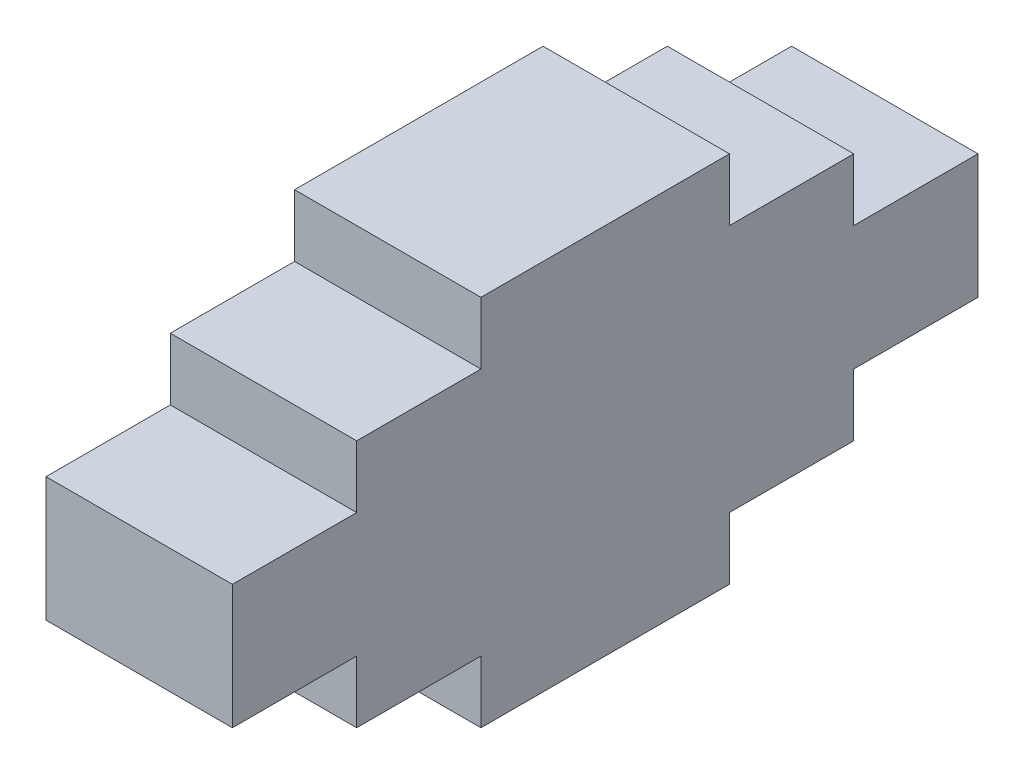
SolidWorks part; units mm, degrees
ref_plane "Front Plane" through (0, 0, 0) normal (0, 0, 1) x (1, 0, 0)
ref_plane "Top Plane" through (0, 0, 0) normal (0, 1, 0) x (1, 0, 0)
ref_plane "Right Plane" through (0, 0, 0) normal (1, 0, 0) x (0, 0, -1)
sketch "Sketch1" plane through (0, 0, 0) normal (1, 0, 0) x (0, 0, -1)
  line L0 (-84.64, 0) -> (83.36, 0) construction
  line L1 (0, 53.84) -> (0, -53.36) construction
  line L2 (-60, -10) -> (-60, 10)
  line L3 (-60, 10) -> (-40, 10)
  line L4 (-40, 10) -> (-40, 20)
  line L5 (-40, 20) -> (-20, 20)
  line L6 (-20, 20) -> (-20, 30)
  line L7 (-20, 30) -> (20, 30)
  line L8 (84.64, 0) -> (-83.36, 0) construction
  line L9 (20, 20) -> (20, 30)
  line L10 (40, 20) -> (20, 20)
  line L11 (40, 10) -> (40, 20)
  line L12 (60, 10) -> (40, 10)
  line L13 (60, -10) -> (60, 10)
  line L14 (0, -53.84) -> (0, 53.36) construction
  line L15 (60, -10) -> (40, -10)
  line L16 (40, -10) -> (40, -20)
  line L17 (40, -20) -> (20, -20)
  line L18 (20, -20) -> (20, -30)
  line L19 (-20, -30) -> (20, -30)
  line L20 (-20, -20) -> (-20, -30)
  line L21 (-40, -20) -> (-20, -20)
  line L22 (-40, -10) -> (-40, -20)
  line L23 (-60, -10) -> (-40, -10)
  point P5 (0, -30)
  point P15 (0, 30)
  point P23 (60, 0)
  point P32 (-60, 0)
  dimension "D1" = 20
  dimension "D2" = 20
  dimension "D3" = 20
  dimension "D4" = 10
  dimension "D5" = 10
  dimension "D6" = 10
extrude "Boss-Extrude1" add sketch "Sketch1" along normal blind 30
